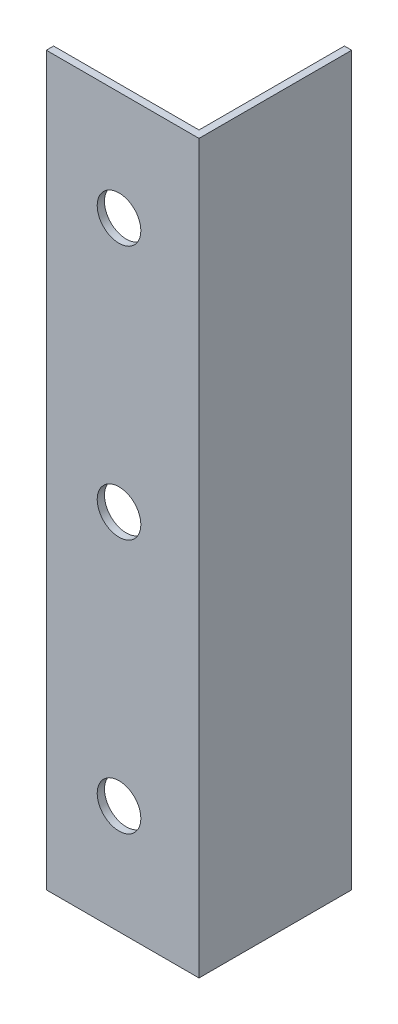
SolidWorks part; units mm, degrees
ref_plane "Front" through (0, 0, 0) normal (0, 0, 1) x (1, 0, 0)
ref_plane "Top" through (0, 0, 0) normal (0, 1, 0) x (1, 0, 0)
ref_plane "Right" through (0, 0, 0) normal (1, 0, 0) x (0, 0, -1)
sketch "Sketch1" plane through (0, 0, 0) normal (0, 1, 0) x (1, 0, 0)
  line L0 (0, 0) -> (0, 1)
  line L3 (0, 1) -> (20, 1)
  line L4 (20, 1) -> (20, 21)
  line L7 (21, 0) -> (0, 0)
  line L8 (21, 0) -> (21, 21)
  line L9 (21, 21) -> (20, 21)
  dimension "D1" = 1
  dimension "D2" = 20
  dimension "D3" = 21
  dimension "D4" = 21
  dimension "D5" = 1
extrude "Boss-Extrude1" add sketch "Sketch1" along normal blind 100 contours L3 L4 L9 L8 L7 L0
sketch "Sketch2" plane through (0, 0, -1) normal (0, 0, -1) x (-1, 0, 0)
  line L0 (0, 100) -> (-20, 100) construction
  line L1 (0, 100) -> (0, 0) construction
  circle A0 centre (-10, 15) radius 3
  circle A1 centre (-10, 50) radius 3
  circle A2 centre (-10, 85) radius 3
  dimension "D5" = 6
  dimension "D1" = 35
  dimension "D2" = 50
  dimension "D3" = 35
  dimension "D4" = 10
extrude "Cut-Extrude1" cut sketch "Sketch2" against normal blind 10
